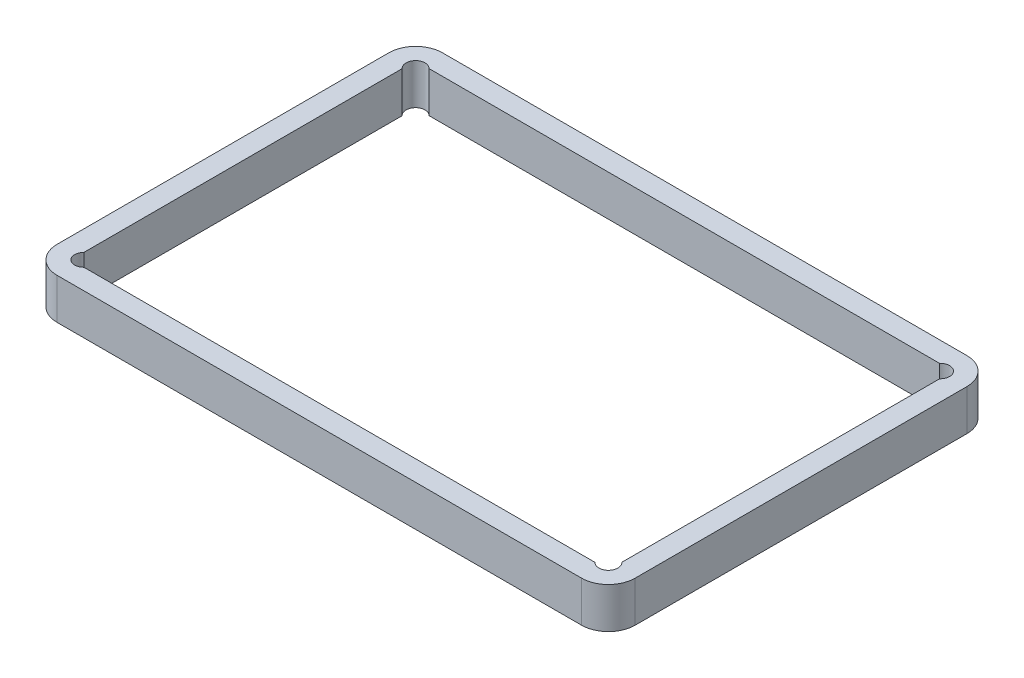
SolidWorks part; units mm, degrees
ref_plane "Front" through (0, 0, 0) normal (0, 0, 1) x (1, 0, 0)
ref_plane "Top" through (0, 0, 0) normal (0, 1, 0) x (1, 0, 0)
ref_plane "Right" through (0, 0, 0) normal (1, 0, 0) x (0, 0, -1)
sketch "Sketch1" plane through (0, 0, 0) normal (0, 1, 0) x (1, 0, 0)
  line L0 (-45, 0) -> (45, 0) construction
  line L1 (-45, 30) -> (45, 30) construction
  line L2 (-45, 30) -> (-45, -30) construction
  line L3 (-45, -30) -> (45, -30) construction
  line L4 (45, 30) -> (45, -30) construction
  line L5 (0, -30) -> (0, 30) construction
  line L6 (41.825, 26.825) -> (41.825, -26.825) construction
  line L7 (-41.825, -26.825) -> (41.825, -26.825) construction
  line L8 (-41.825, 26.825) -> (-41.825, -26.825) construction
  line L9 (-41.825, 26.825) -> (41.825, 26.825) construction
  line L10 (40.825, 25.825) -> (40.825, -25.825) construction
  line L11 (-40.825, -25.825) -> (40.825, -25.825) construction
  line L12 (-40.825, 25.825) -> (-40.825, -25.825) construction
  line L13 (-40.825, 25.825) -> (40.825, 25.825) construction
  line L14 (40.825, 21.65) -> (45, 21.65) construction
  line L15 (40.825, -21.65) -> (45, -21.65) construction
  line L16 (36.65, -25.825) -> (36.65, -30) construction
  line L17 (-36.65, -25.825) -> (-36.65, -30) construction
  line L18 (-40.825, -21.65) -> (-45, -21.65) construction
  line L19 (-36.65, 25.825) -> (-36.65, 30) construction
  line L20 (-40.825, 21.65) -> (-45, 21.65) construction
  line L21 (36.65, 25.825) -> (36.65, 30) construction
  line L22 (40.825, -25.825) -> (41.825, -25.825) construction
  circle A0 centre (-40.825, -25.825) radius 1 construction
  circle A1 centre (40.825, -25.825) radius 1 construction
  circle A2 centre (40.825, 25.825) radius 1 construction
  circle A3 centre (-40.825, 25.825) radius 1 construction
  circle A4 centre (40.825, -25.825) radius 4.175 construction
  circle A5 centre (40.825, 25.825) radius 4.175 construction
  circle A6 centre (-40.825, 25.825) radius 4.175 construction
  circle A7 centre (-40.825, -25.825) radius 4.175 construction
  dimension "D1" = 90
  dimension "D2" = 60
  dimension "D4" = 1
  dimension "D3" = 3.175
sketch "Sketch2" plane through (0, 0, 0) normal (0, 1, 0) x (1, 0, 0)
  line L0 (-45, 30) -> (-45, -30) construction
  line L1 (-45, -30) -> (45, -30) construction
  line L2 (45, 30) -> (45, -30) construction
  line L3 (-45, 30) -> (45, 30) construction
  line L12 (-41.825, -25.825) -> (-41.825, 25.825)
  line L13 (-40.825, 26.825) -> (40.825, 26.825)
  line L14 (41.825, 25.825) -> (41.825, -25.825)
  line L15 (40.825, -26.825) -> (-40.825, -26.825)
  line L16 (-45, 25.825) -> (-45, -25.825)
  line L17 (-40.825, -30) -> (40.825, -30)
  line L18 (45, 25.825) -> (45, -25.825)
  line L19 (-40.825, 30) -> (40.825, 30)
  circle A0 centre (40.825, 25.825) radius 4.175 construction
  circle A1 centre (40.825, 25.825) radius 1 construction
  circle A2 centre (-40.825, 25.825) radius 4.175 construction
  circle A3 centre (-40.825, 25.825) radius 1 construction
  arc A6 (45, 25.825) -> (40.825, 30) centre (40.825, 25.825) ccw
  arc A7 (41.825, 25.825) -> (40.825, 26.825) centre (40.825, 25.825) ccw
  arc A8 (-40.825, 30) -> (-45, 25.825) centre (-40.825, 25.825) ccw
  arc A9 (-40.825, 26.825) -> (-41.825, 25.825) centre (-40.825, 25.825) ccw
  circle A12 centre (-40.825, -25.825) radius 1 construction
  circle A13 centre (40.825, -25.825) radius 1 construction
  arc A14 (-41.825, -25.825) -> (-40.825, -26.825) centre (-40.825, -25.825) ccw
  arc A15 (40.825, -26.825) -> (41.825, -25.825) centre (40.825, -25.825) ccw
  arc A17 (-45, -25.825) -> (-40.825, -30) centre (-40.825, -25.825) ccw
  arc A18 (40.825, -30) -> (45, -25.825) centre (40.825, -25.825) ccw
extrude "Boss-Extrude3" add sketch "Sketch2" along normal blind 6.35
sketch "Sketch5" plane through (0, 0, 0) normal (0, -1, 0) x (1, 0, 0)
  circle A0 centre (-40.825, 25.825) radius 1.4224 construction
  circle A1 centre (-40.825, 25.825) radius 1.4224
  circle A2 centre (40.825, 25.8149) radius 1.4732 construction
  circle A3 centre (40.825, -25.825) radius 1.4732 construction
  circle A4 centre (-40.825, -25.8136) radius 1.4732 construction
  circle A5 centre (40.825, 25.8149) radius 1.4732
  circle A6 centre (40.825, -25.825) radius 1.4732
  circle A7 centre (-40.825, -25.8136) radius 1.4732
extrude "Cut-Extrude2" cut sketch "Sketch5" against normal through all
